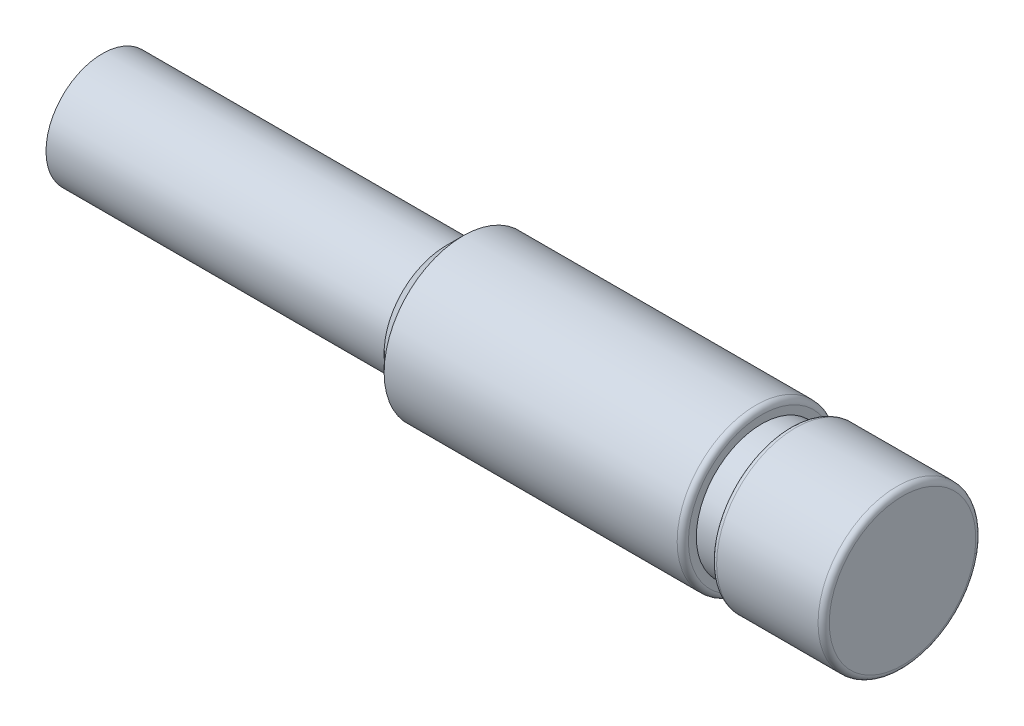
SolidWorks part; units mm, degrees
ref_plane "Plano frontal" through (0, 0, 0) normal (0, 0, 1) x (1, 0, 0)
ref_plane "Plano superior" through (0, 0, 0) normal (0, 1, 0) x (1, 0, 0)
ref_plane "Plano direito" through (0, 0, 0) normal (1, 0, 0) x (0, 0, -1)
sketch "Esboço1" plane through (0, 0, 0) normal (0, 0, 1) x (1, 0, 0)
  line L0 (0, 0) -> (71, 0)
  line L1 (71, 0) -> (71, 7)
  line L2 (71, 7) -> (61, 7)
  line L3 (61, 7) -> (61, 5.8)
  line L4 (61, 5.8) -> (58.5, 5.8)
  line L5 (58.5, 5.8) -> (58.5, 7)
  line L6 (58.5, 7) -> (30.5, 7)
  line L7 (30.5, 7) -> (30.5, 5)
  line L8 (30.5, 5) -> (0, 5)
  line L9 (0, 5) -> (0, 0)
  point P3 (66, 7)
  point P12 (44.5, 7)
  dimension "D1" = 5
  dimension "D2" = 71
  dimension "D3" = 10
  dimension "D4" = 7
  dimension "D5" = 2.5
  dimension "D6" = 1.2
  dimension "D7" = 28
revolve "Revolução1" add sketch "Esboço1" angle 360 about L0
cosmetic thread "Representação de rosca4" parameters "D1"=27.5, "D2"=11.797
sketch "Esboço2" plane through (0, 0, 0) normal (-1, 0, 0) x (0, 0, 1)
  circle A2 centre (0, 0) radius 3
  dimension "D1" = 6
extrude "Corte-extrusão1" cut sketch "Esboço2" against normal blind 3.6 contours A2
chamfer "Chanfro2" distance 1.5 angle 65 1 edges at (0, 0, 3)
chamfer "Chanfro3" distance 1.5 angle 45 1 edges at (30.5, 0, 7)
fillet "Filete3" radius 0.5 3 edges at (58.5, 0, 7) (71, 0, 7) (61, 0, 7)
